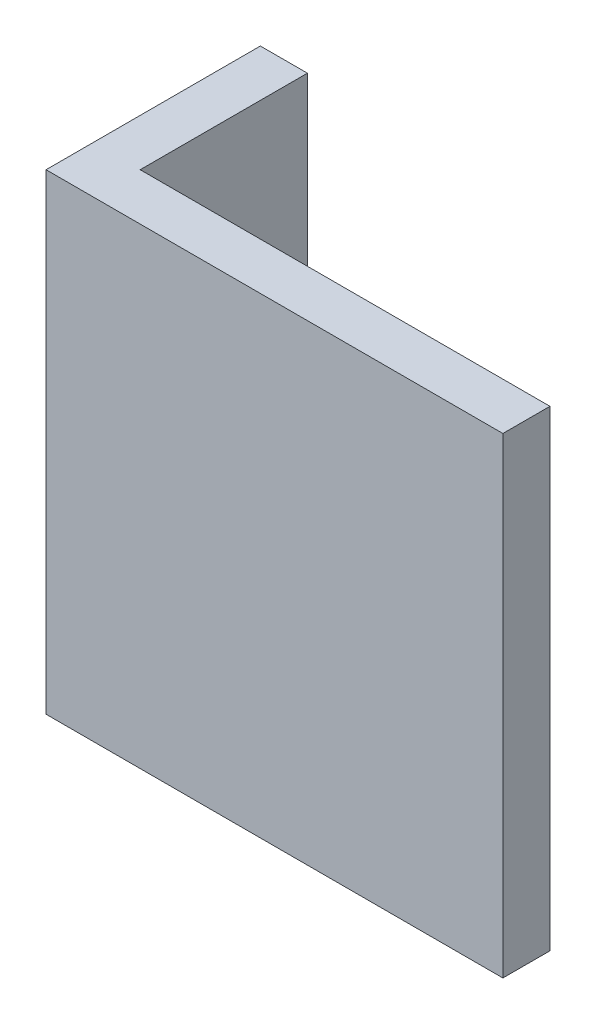
SolidWorks part; units mm, degrees
ref_plane "Front Plane" through (0, 0, 0) normal (0, 0, 1) x (1, 0, 0)
ref_plane "Top Plane" through (0, 0, 0) normal (0, 1, 0) x (1, 0, 0)
ref_plane "Right Plane" through (0, 0, 0) normal (1, 0, 0) x (0, 0, -1)
sketch "Sketch1" plane through (0, 0, 0) normal (0, 1, 0) x (1, 0, 0)
  line L2 (-2.7551, -8.5885) -> (-2.7551, -22.2485)
  line L3 (-2.7551, -22.2485) -> (26.3649, -22.2485)
  line L6 (0.2449, -8.5885) -> (0.2449, -19.2485)
  line L7 (0.2449, -19.2485) -> (26.3649, -19.2485)
  line L9 (26.3649, -19.2485) -> (26.3649, -22.2485)
  line L10 (-2.7551, -8.5885) -> (0.2449, -8.5885)
  dimension "D2" = 10.66
  dimension "D3" = 3
  dimension "D4" = 26.12
  dimension "D6" = 3
extrude "Boss-Extrude1" add sketch "Sketch1" along normal blind 30.06
